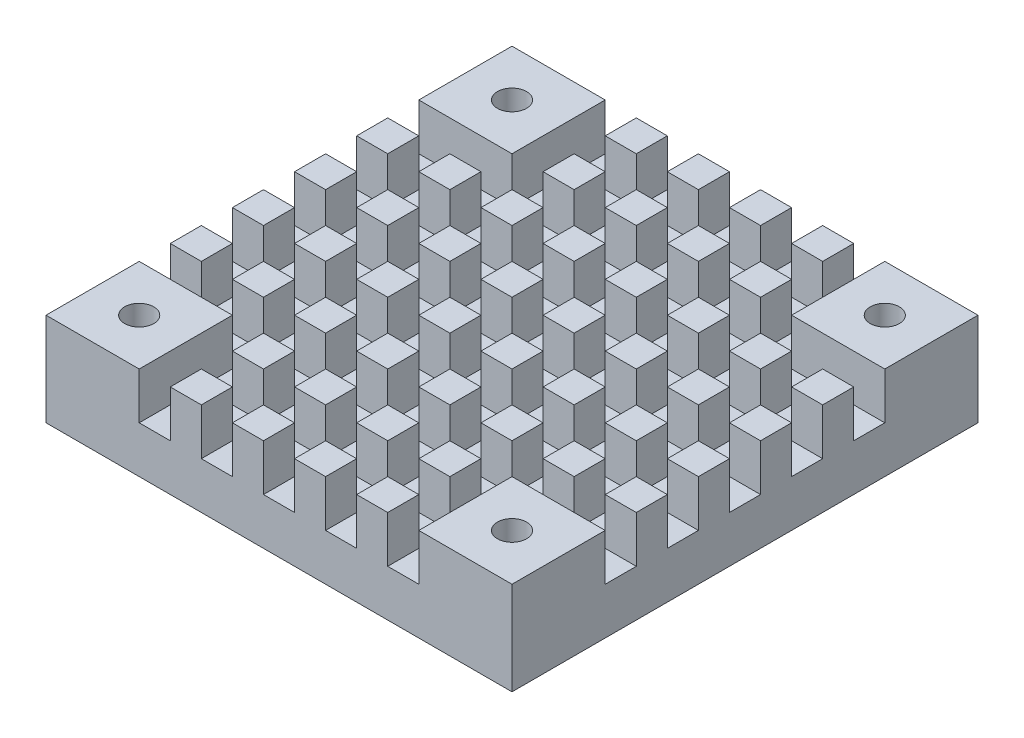
SolidWorks part; units mm, degrees
ref_plane "前视基准面" through (0, 0, 0) normal (0, 0, 1) x (1, 0, 0)
ref_plane "上视基准面" through (0, 0, 0) normal (0, 1, 0) x (1, 0, 0)
ref_plane "右视基准面" through (0, 0, 0) normal (1, 0, 0) x (0, 0, -1)
other "Configuration Table"
sketch "草图2" plane through (0, 0, 0) normal (0, 1, 0) x (1, 0, 0)
  line L1 (-20, -20) -> (20, -20)
  line L2 (-20, -20) -> (-20, 20)
  line L3 (-20, 20) -> (20, 20)
  line L4 (20, -20) -> (20, 20)
  line L5 (-20, -20) -> (20, 20) construction
  line L6 (-20, 20) -> (20, -20) construction
  line L7 (-16, -16) -> (16, -16) construction
  line L8 (-16, -16) -> (-16, 16) construction
  line L9 (-16, 16) -> (16, 16) construction
  line L10 (16, -16) -> (16, 16) construction
  line L11 (-16, -16) -> (16, 16) construction
  line L12 (-16, 16) -> (16, -16) construction
  circle A0 centre (-16, 16) radius 1.25
  circle A1 centre (16, 16) radius 1.25
  circle A2 centre (16, -16) radius 1.25
  circle A3 centre (-16, -16) radius 1.25
  point P0 (0, 0)
  point P5 (0, 0)
  point P21 (0, 0)
  dimension "D3" = 2.5
  dimension "D1" = 40
  dimension "D2" = 32
  dimension "D4" = 4
extrude "凸台-拉伸1" add sketch "草图2" along normal blind 4
sketch "草图3" plane through (0, 4, 0) normal (0, 1, 0) x (1, 0, 0)
  line L1 (9.3333, -14.6667) -> (6.6667, -14.6667)
  line L4 (20, -20) -> (20, 20)
  line L5 (20, 20) -> (-20, 20)
  line L6 (-20, 20) -> (-20, -20)
  line L7 (-20, -20) -> (20, -20)
  line L8 (20, -20) -> (20, -12)
  line L9 (20, 20) -> (12, 20)
  line L10 (-20, 20) -> (-20, 12)
  line L11 (-20, -20) -> (-12, -20)
  line L12 (20, 9.3333) -> (17.3333, 9.3333)
  line L13 (20, 6.6667) -> (17.3333, 6.6667)
  line L14 (20, 4) -> (17.3333, 4)
  line L15 (20, 1.3333) -> (17.3333, 1.3333)
  line L17 (20, -1.3333) -> (17.3333, -1.3333)
  line L18 (-20, 12) -> (-12, 12)
  line L19 (20, -4) -> (17.3333, -4)
  line L20 (20, -6.6667) -> (17.3333, -6.6667)
  line L21 (20, -9.3333) -> (17.3333, -9.3333)
  line L23 (-12, 9.3333) -> (-14.6667, 9.3333)
  line L25 (-12, 6.6667) -> (-14.6667, 6.6667)
  line L29 (-12, 20) -> (-12, 12)
  line L30 (-9.3333, 20) -> (-9.3333, 17.3333)
  line L31 (-6.6667, 20) -> (-6.6667, 17.3333)
  line L32 (-20, 4) -> (-20, 1.3333)
  line L33 (-4, 20) -> (-4, 17.3333)
  line L34 (-1.3333, 20) -> (-1.3333, 17.3333)
  line L35 (1.3333, 20) -> (1.3333, 17.3333)
  line L36 (4, 20) -> (4, 17.3333)
  line L37 (6.6667, 20) -> (6.6667, 17.3333)
  line L38 (9.3333, 20) -> (9.3333, 17.3333)
  line L39 (12, 20) -> (12, 12)
  line L40 (-12, 4) -> (-14.6667, 4)
  line L46 (9.3333, -17.3333) -> (6.6667, -17.3333)
  line L47 (-17.3333, 9.3333) -> (-17.3333, 6.6667)
  line L48 (-14.6667, 9.3333) -> (-14.6667, 6.6667)
  line L51 (9.3333, 17.3333) -> (6.6667, 17.3333)
  line L52 (9.3333, 14.6667) -> (6.6667, 14.6667)
  line L53 (12, 12) -> (20, 12)
  line L54 (14.6667, 9.3333) -> (14.6667, 6.6667)
  line L55 (17.3333, 9.3333) -> (17.3333, 6.6667)
  line L56 (-12, 1.3333) -> (-14.6667, 1.3333)
  line L57 (12, -12) -> (20, -12)
  line L59 (-17.3333, 17.3333) -> (-17.3333, 14.6667) [skipped]
  line L60 (-14.6667, 17.3333) -> (-14.6667, 14.6667) [skipped]
  line L61 (17.3333, 17.3333) -> (17.3333, 14.6667) [skipped]
  line L62 (14.6667, 17.3333) -> (14.6667, 14.6667) [skipped]
  line L63 (17.3333, 17.3333) -> (14.6667, 17.3333) [skipped]
  line L64 (17.3333, 14.6667) -> (14.6667, 14.6667) [skipped]
  line L65 (20, -14.6667) -> (17.3333, -14.6667) [skipped]
  line L66 (17.3333, -17.3333) -> (14.6667, -17.3333) [skipped]
  line L67 (-12, -1.3333) -> (-14.6667, -1.3333)
  line L68 (-12, -4) -> (-14.6667, -4)
  line L69 (-12, -6.6667) -> (-14.6667, -6.6667)
  line L70 (-12, -9.3333) -> (-14.6667, -9.3333)
  line L71 (-12, -12) -> (-20, -12)
  line L72 (-9.3333, -20) -> (-6.6667, -20)
  line L73 (-20, -12) -> (-20, -20)
  line L74 (-12, -12) -> (-12, -20)
  line L75 (-9.3333, -12) -> (-9.3333, -14.6667)
  line L76 (-6.6667, -12) -> (-6.6667, -14.6667)
  line L77 (-4, -12) -> (-4, -14.6667)
  line L78 (-1.3333, -12) -> (-1.3333, -14.6667)
  line L79 (1.3333, -12) -> (1.3333, -14.6667)
  line L80 (4, -12) -> (4, -14.6667)
  line L81 (6.6667, -12) -> (6.6667, -14.6667)
  line L82 (9.3333, -12) -> (9.3333, -14.6667)
  line L83 (12, -12) -> (12, -20)
  line L84 (20, -9.3333) -> (20, -6.6667)
  line L85 (9.3333, 12) -> (6.6667, 12)
  line L86 (9.3333, 9.3333) -> (6.6667, 9.3333)
  line L87 (9.3333, 6.6667) -> (6.6667, 6.6667)
  line L88 (9.3333, 4) -> (6.6667, 4)
  line L89 (9.3333, 1.3333) -> (6.6667, 1.3333)
  line L90 (9.3333, -1.3333) -> (6.6667, -1.3333)
  line L91 (9.3333, -4) -> (6.6667, -4)
  line L92 (9.3333, -6.6667) -> (6.6667, -6.6667)
  line L93 (9.3333, -9.3333) -> (6.6667, -9.3333)
  line L94 (9.3333, -12) -> (6.6667, -12)
  line L95 (12, -20) -> (20, -20)
  line L96 (-20, 9.3333) -> (-20, 6.6667)
  line L97 (-12, 9.3333) -> (-12, 6.6667)
  line L98 (-9.3333, 9.3333) -> (-9.3333, 6.6667)
  line L99 (-6.6667, 9.3333) -> (-6.6667, 6.6667)
  line L100 (-4, 9.3333) -> (-4, 6.6667)
  line L101 (-1.3333, 9.3333) -> (-1.3333, 6.6667)
  line L102 (1.3333, 9.3333) -> (1.3333, 6.6667)
  line L103 (4, 9.3333) -> (4, 6.6667)
  line L104 (6.6667, 9.3333) -> (6.6667, 6.6667)
  line L105 (9.3333, 9.3333) -> (9.3333, 6.6667)
  line L106 (12, 9.3333) -> (12, 6.6667)
  line L107 (20, 12) -> (20, 20)
  line L108 (-12, 20) -> (-20, 20)
  line L109 (9.3333, 20) -> (6.6667, 20)
  line L110 (20, 12) -> (12, 12) [skipped]
  line L111 (20, -12) -> (12, -12) [skipped]
  line L112 (-17.3333, 4) -> (-17.3333, 1.3333)
  line L113 (-14.6667, 4) -> (-14.6667, 1.3333)
  line L114 (-12, 4) -> (-12, 1.3333)
  line L115 (-9.3333, 4) -> (-9.3333, 1.3333)
  line L116 (-6.6667, 4) -> (-6.6667, 1.3333)
  line L117 (-4, 4) -> (-4, 1.3333)
  line L118 (-1.3333, 4) -> (-1.3333, 1.3333)
  line L119 (1.3333, 4) -> (1.3333, 1.3333)
  line L120 (4, 4) -> (4, 1.3333)
  line L121 (6.6667, 4) -> (6.6667, 1.3333)
  line L122 (9.3333, 4) -> (9.3333, 1.3333)
  line L123 (12, 4) -> (12, 1.3333)
  line L124 (14.6667, 4) -> (14.6667, 1.3333)
  line L125 (17.3333, 4) -> (17.3333, 1.3333)
  line L126 (20, 6.6667) -> (20, 9.3333)
  line L127 (-20, -1.3333) -> (-20, -4)
  line L128 (-17.3333, -1.3333) -> (-17.3333, -4)
  line L129 (-14.6667, -1.3333) -> (-14.6667, -4)
  line L130 (-12, -1.3333) -> (-12, -4)
  line L131 (-9.3333, -1.3333) -> (-9.3333, -4)
  line L132 (-6.6667, -1.3333) -> (-6.6667, -4)
  line L133 (-4, -1.3333) -> (-4, -4)
  line L134 (-1.3333, -1.3333) -> (-1.3333, -4)
  line L135 (1.3333, -1.3333) -> (1.3333, -4)
  line L136 (4, -1.3333) -> (4, -4)
  line L137 (6.6667, -1.3333) -> (6.6667, -4)
  line L138 (9.3333, -1.3333) -> (9.3333, -4)
  line L139 (12, -1.3333) -> (12, -4)
  line L140 (14.6667, -1.3333) -> (14.6667, -4)
  line L141 (17.3333, -1.3333) -> (17.3333, -4)
  line L142 (20, 1.3333) -> (20, 4)
  line L143 (-20, -6.6667) -> (-20, -9.3333)
  line L144 (-17.3333, -6.6667) -> (-17.3333, -9.3333)
  line L145 (-14.6667, -6.6667) -> (-14.6667, -9.3333)
  line L146 (-12, -6.6667) -> (-12, -9.3333)
  line L147 (-9.3333, -6.6667) -> (-9.3333, -9.3333)
  line L148 (-6.6667, -6.6667) -> (-6.6667, -9.3333)
  line L149 (-4, -6.6667) -> (-4, -9.3333)
  line L150 (-1.3333, -6.6667) -> (-1.3333, -9.3333)
  line L151 (1.3333, -6.6667) -> (1.3333, -9.3333)
  line L152 (4, -6.6667) -> (4, -9.3333)
  line L153 (6.6667, -6.6667) -> (6.6667, -9.3333)
  line L154 (9.3333, -6.6667) -> (9.3333, -9.3333)
  line L155 (12, -6.6667) -> (12, -9.3333)
  line L156 (14.6667, -6.6667) -> (14.6667, -9.3333)
  line L157 (17.3333, -6.6667) -> (17.3333, -9.3333)
  line L158 (20, -4) -> (20, -1.3333)
  line L159 (-6.6667, 20) -> (-9.3333, 20)
  line L160 (-6.6667, 17.3333) -> (-9.3333, 17.3333)
  line L161 (-6.6667, 14.6667) -> (-9.3333, 14.6667)
  line L162 (-6.6667, 12) -> (-9.3333, 12)
  line L163 (-6.6667, 9.3333) -> (-9.3333, 9.3333)
  line L164 (-6.6667, 6.6667) -> (-9.3333, 6.6667)
  line L165 (-6.6667, 4) -> (-9.3333, 4)
  line L166 (-6.6667, 1.3333) -> (-9.3333, 1.3333)
  line L167 (-6.6667, -1.3333) -> (-9.3333, -1.3333)
  line L168 (-6.6667, -4) -> (-9.3333, -4)
  line L169 (-6.6667, -6.6667) -> (-9.3333, -6.6667)
  line L170 (-6.6667, -9.3333) -> (-9.3333, -9.3333)
  line L171 (-6.6667, -12) -> (-9.3333, -12)
  line L172 (-6.6667, -14.6667) -> (-9.3333, -14.6667)
  line L173 (-6.6667, -17.3333) -> (-9.3333, -17.3333)
  line L174 (-4, -20) -> (-1.3333, -20)
  line L175 (-1.3333, 20) -> (-4, 20)
  line L176 (-1.3333, 17.3333) -> (-4, 17.3333)
  line L177 (-1.3333, 14.6667) -> (-4, 14.6667)
  line L178 (-1.3333, 12) -> (-4, 12)
  line L179 (-1.3333, 9.3333) -> (-4, 9.3333)
  line L180 (-1.3333, 6.6667) -> (-4, 6.6667)
  line L181 (-1.3333, 4) -> (-4, 4)
  line L182 (-1.3333, 1.3333) -> (-4, 1.3333)
  line L183 (-1.3333, -1.3333) -> (-4, -1.3333)
  line L184 (-1.3333, -4) -> (-4, -4)
  line L185 (-1.3333, -6.6667) -> (-4, -6.6667)
  line L186 (-1.3333, -9.3333) -> (-4, -9.3333)
  line L187 (-1.3333, -12) -> (-4, -12)
  line L188 (-1.3333, -14.6667) -> (-4, -14.6667)
  line L189 (-1.3333, -17.3333) -> (-4, -17.3333)
  line L190 (1.3333, -20) -> (4, -20)
  line L191 (4, 20) -> (1.3333, 20)
  line L192 (4, 17.3333) -> (1.3333, 17.3333)
  line L193 (4, 14.6667) -> (1.3333, 14.6667)
  line L194 (4, 12) -> (1.3333, 12)
  line L195 (4, 9.3333) -> (1.3333, 9.3333)
  line L196 (4, 6.6667) -> (1.3333, 6.6667)
  line L197 (4, 4) -> (1.3333, 4)
  line L198 (4, 1.3333) -> (1.3333, 1.3333)
  line L199 (4, -1.3333) -> (1.3333, -1.3333)
  line L200 (4, -4) -> (1.3333, -4)
  line L201 (4, -6.6667) -> (1.3333, -6.6667)
  line L202 (4, -9.3333) -> (1.3333, -9.3333)
  line L203 (4, -12) -> (1.3333, -12)
  line L204 (4, -14.6667) -> (1.3333, -14.6667)
  line L205 (4, -17.3333) -> (1.3333, -17.3333)
  line L206 (6.6667, -20) -> (9.3333, -20)
  line L207 (-17.3333, 9.3333) -> (-20, 9.3333)
  line L208 (-17.3333, 6.6667) -> (-20, 6.6667)
  line L209 (-17.3333, 4) -> (-20, 4)
  line L210 (-17.3333, 1.3333) -> (-20, 1.3333)
  line L211 (-17.3333, -1.3333) -> (-20, -1.3333)
  line L212 (-17.3333, -4) -> (-20, -4)
  line L213 (-17.3333, -6.6667) -> (-20, -6.6667)
  line L214 (-17.3333, -9.3333) -> (-20, -9.3333)
  line L215 (14.6667, 9.3333) -> (12, 9.3333)
  line L216 (14.6667, 6.6667) -> (12, 6.6667)
  line L217 (14.6667, 4) -> (12, 4)
  line L218 (14.6667, 1.3333) -> (12, 1.3333)
  line L219 (14.6667, -1.3333) -> (12, -1.3333)
  line L220 (14.6667, -4) -> (12, -4)
  line L221 (14.6667, -6.6667) -> (12, -6.6667)
  line L222 (14.6667, -9.3333) -> (12, -9.3333)
  line L223 (-9.3333, -17.3333) -> (-9.3333, -20)
  line L224 (-6.6667, -17.3333) -> (-6.6667, -20)
  line L225 (-4, -17.3333) -> (-4, -20)
  line L226 (-1.3333, -17.3333) -> (-1.3333, -20)
  line L227 (1.3333, -17.3333) -> (1.3333, -20)
  line L228 (4, -17.3333) -> (4, -20)
  line L229 (6.6667, -17.3333) -> (6.6667, -20)
  line L230 (9.3333, -17.3333) -> (9.3333, -20)
  line L231 (-9.3333, 14.6667) -> (-9.3333, 12)
  line L232 (-6.6667, 14.6667) -> (-6.6667, 12)
  line L233 (-4, 14.6667) -> (-4, 12)
  line L234 (-1.3333, 14.6667) -> (-1.3333, 12)
  line L235 (1.3333, 14.6667) -> (1.3333, 12)
  line L236 (4, 14.6667) -> (4, 12)
  line L237 (6.6667, 14.6667) -> (6.6667, 12)
  line L238 (9.3333, 14.6667) -> (9.3333, 12)
  circle A0 centre (16, 16) radius 1.25 construction
  circle A1 centre (16, -16) radius 1.25 construction
  circle A2 centre (-16, -16) radius 1.25 construction
  circle A3 centre (-16, 16) radius 1.25 construction
  circle A4 centre (16, 16) radius 1.25
  circle A5 centre (16, -16) radius 1.25
  circle A6 centre (-16, -16) radius 1.25
  circle A7 centre (-16, 16) radius 1.25
  dimension "D2" = 15
  dimension "D3" = 15
  dimension "D1" = 0
extrude "凸台-拉伸2" add sketch "草图3" along normal blind 4
